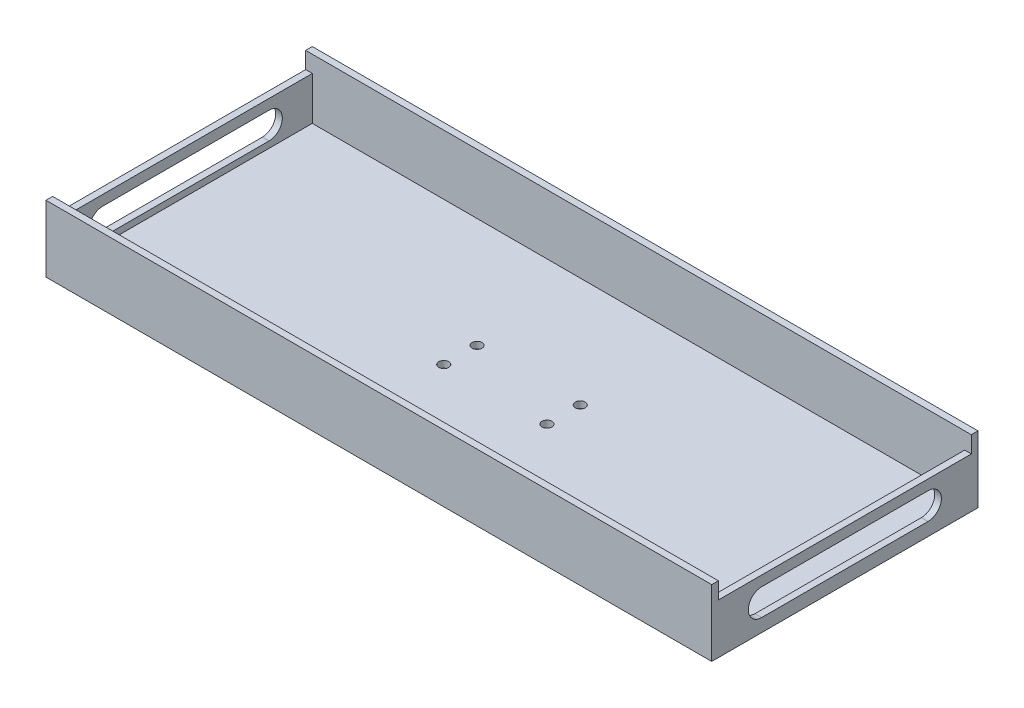
SolidWorks part; units mm, degrees
ref_plane "Ön Düzlem" through (0, 0, 0) normal (0, 0, 1) x (1, 0, 0)
ref_plane "Üst Düzlem" through (0, 0, 0) normal (0, 1, 0) x (1, 0, 0)
ref_plane "Sağ Düzlem" through (0, 0, 0) normal (1, 0, 0) x (0, 0, -1)
sketch "Çizim4" plane through (0, 0, 0) normal (0, 1, 0) x (1, 0, 0)
  line L1 (-200, -40) -> (0, -40)
  line L2 (-200, -40) -> (-200, 40)
  line L3 (-200, 40) -> (0, 40)
  line L4 (0, -40) -> (0, 40)
  line L5 (-200, -40) -> (0, 40) construction
  line L6 (-200, 40) -> (0, -40) construction
  point P0 (-100, 0)
  dimension "D1" = 80
  dimension "D2" = 200
extrude "Yükseklik-Ekstrüzyon3" add sketch "Çizim4" along normal mid plane 20
ref_plane "Düzlem1" through (-100, 0, 0) normal (1, 0, 0) x (0, 0, -1)
shell "İç Boşaltma1" thickness 2
sketch "Çizim5" plane through (0, 0, 0) normal (1, 0, 0) x (0, 0, -1)
  line L1 (-38, 10) -> (38, 10)
  line L2 (-38, 10) -> (-38, 5)
  line L3 (-38, 5) -> (38, 5)
  line L4 (38, 10) -> (38, 5)
  line L5 (-38, 10) -> (38, 5) construction
  line L6 (-38, 5) -> (38, 10) construction
  line L7 (-40, 10) -> (40, 10) construction
  line L10 (40, 10) -> (40, -10) construction
  line L11 (-40, 10) -> (-40, -10) construction
  point P0 (0.6869, 7.4548)
  dimension "D1" = 5
  dimension "D2" = 2
  dimension "D3" = 2
extrude "Kes-Ekstrüzyon1" cut sketch "Çizim5" against normal blind 200
sketch "Çizim8" plane through (0, -10, 0) normal (0, -1, 0) x (1, 0, 0)
  line L2 (-100, -11) -> (-100, 11) construction
  circle A0 centre (-84.5, 5) radius 1.5
  circle A1 centre (-84.5, -5) radius 1.5
  circle A2 centre (-115.5, -5) radius 1.5
  circle A3 centre (-115.5, 5) radius 1.5
  point P4 (0, 0)
  dimension "D2" = 3
  dimension "D3" = 3
  dimension "D7" = 15.5
  dimension "D1" = 10
  dimension "D4" = 5
  dimension "D5" = 15.5
  dimension "D6" = 31
extrude "Kes-Ekstrüzyon3" cut sketch "Çizim8" against normal blind 39
sketch "Çizim10" plane through (0, 0, 0) normal (1, 0, 0) x (0, 0, -1)
  line L0 (25, -2.0663) -> (10, -2.0663) construction
  line L1 (25, -6.0663) -> (10, -6.0663)
  line L2 (25, 1.9337) -> (10, 1.9337)
  line L5 (-10, 1.9337) -> (-25, 1.9337)
  line L6 (-10, 1.9337) -> (10, 1.9337)
  line L7 (-10, -6.0663) -> (-25, -6.0663)
  line L8 (10, -6.0663) -> (-10, -6.0663)
  arc A0 (25, -6.0663) -> (25, 1.9337) centre (25, -2.0663) ccw
  arc A1 (-25, 1.9337) -> (-25, -6.0663) centre (-25, -2.0663) ccw
  point P2 (0, -2.0663)
  dimension "D1" = 4
  dimension "D2" = 50
extrude "Kes-Ekstrüzyon4" cut sketch "Çizim10" against normal blind 235
sketch "Çizim12" plane through (0, -10, 0) normal (0, -1, 0) x (1, 0, 0)
  text T0 "<b>CREATİNY             ADANA</b>" font "Century Gothic" height 10
extrude "Yükseklik-Ekstrüzyon4" add sketch "Çizim12" along normal blind 2
ref_plane "Düzlem2" through (0, -12, 0) normal (0, 1, 0) x (1, 0, 0)
sketch "Çizim13" plane through (0, -12, 0) normal (0, 1, 0) x (1, 0, 0)
  text T0 "<b>CREATİNY            ADANA</b>" font "Century Gothic" height 10
  text T1 "<b>♥</b>" font "Century Gothic" height 30
  text T2 "<b>♥</b>" font "Century Gothic" height 30
  point P3 (0, 0)
extrude "Yükseklik-Ekstrüzyon5" add sketch "Çizim13" along normal blind 2
